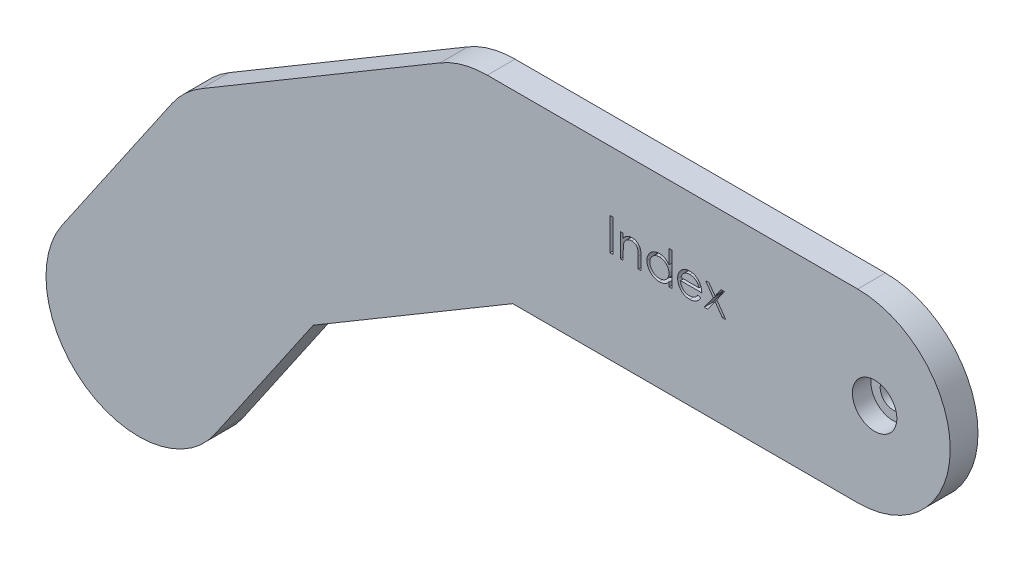
SolidWorks part; units mm, degrees
ref_plane "Front Plane" through (0, 0, 0) normal (0, 0, 1) x (1, 0, 0)
ref_plane "Top Plane" through (0, 0, 0) normal (0, 1, 0) x (1, 0, 0)
ref_plane "Right Plane" through (0, 0, 0) normal (1, 0, 0) x (0, 0, -1)
sketch "Sketch1" plane through (0, 0, 0) normal (0, 0, 1) x (1, 0, 0)
  line L0 (0, 0) -> (40, 0) construction
  line L2 (0, 10) -> (40, 10)
  line L3 (0, -10) -> (40, -10)
  arc A0 (0, 10) -> (0, -10) centre (0, 0) ccw
  arc A1 (40, -10) -> (40, 10) centre (40, 0) ccw
  point P5 (20, 0)
extrude "Boss-Extrude1" add sketch "Sketch1" along normal blind 3
sketch "Sketch2" plane through (0, 0, 0) normal (0, 0, 1) x (1, 0, 0)
  line L0 (0, 0) -> (-25.7976, -15.3128) construction
  line L2 (5.1043, -8.5992) -> (-20.6934, -23.912)
  line L3 (-5.1043, 8.5992) -> (-30.9019, -6.7136)
  arc A0 (5.1043, -8.5992) -> (-5.1043, 8.5992) centre (0, 0) ccw
  arc A1 (-30.9019, -6.7136) -> (-20.6934, -23.912) centre (-25.7976, -15.3128) ccw
  point P5 (-12.8988, -7.6564)
extrude "Boss-Extrude2" add sketch "Sketch2" along normal blind 3
sketch "Sketch3" plane through (0, 0, 0) normal (0, 0, 1) x (1, 0, 0)
  line L0 (-25.7976, -15.3128) -> (-37.6619, -32.6266) construction
  line L2 (-17.5486, -20.9655) -> (-29.4128, -38.2793)
  line L3 (-34.0467, -9.6601) -> (-45.911, -26.9739)
  arc A0 (-17.5486, -20.9655) -> (-34.0467, -9.6601) centre (-25.7976, -15.3128) ccw
  arc A1 (-45.911, -26.9739) -> (-29.4128, -38.2793) centre (-37.6619, -32.6266) ccw
  point P5 (-31.7298, -23.9697)
extrude "Boss-Extrude4" add sketch "Sketch3" along normal blind 3
sketch "Sketch4" plane through (0, 0, 0) normal (0, 0, 1) x (1, 0, 0)
  circle A0 centre (41.8354, 0) radius 1.4
extrude "Cut-Extrude5" cut sketch "Sketch4" along normal blind 3
sketch "Sketch5" plane through (0, 0, 3) normal (0, 0, 1) x (1, 0, 0)
  circle A0 centre (41.8354, 0) radius 2.4
extrude "Cut-Extrude6" cut sketch "Sketch5" against normal blind 2
sketch "Sketch7" plane through (0, 0, 3) normal (0, 0, 1) x (1, 0, 0)
  text T0 "Index"
extrude "Cut-Extrude7" cut sketch "Sketch7" against normal blind 1
